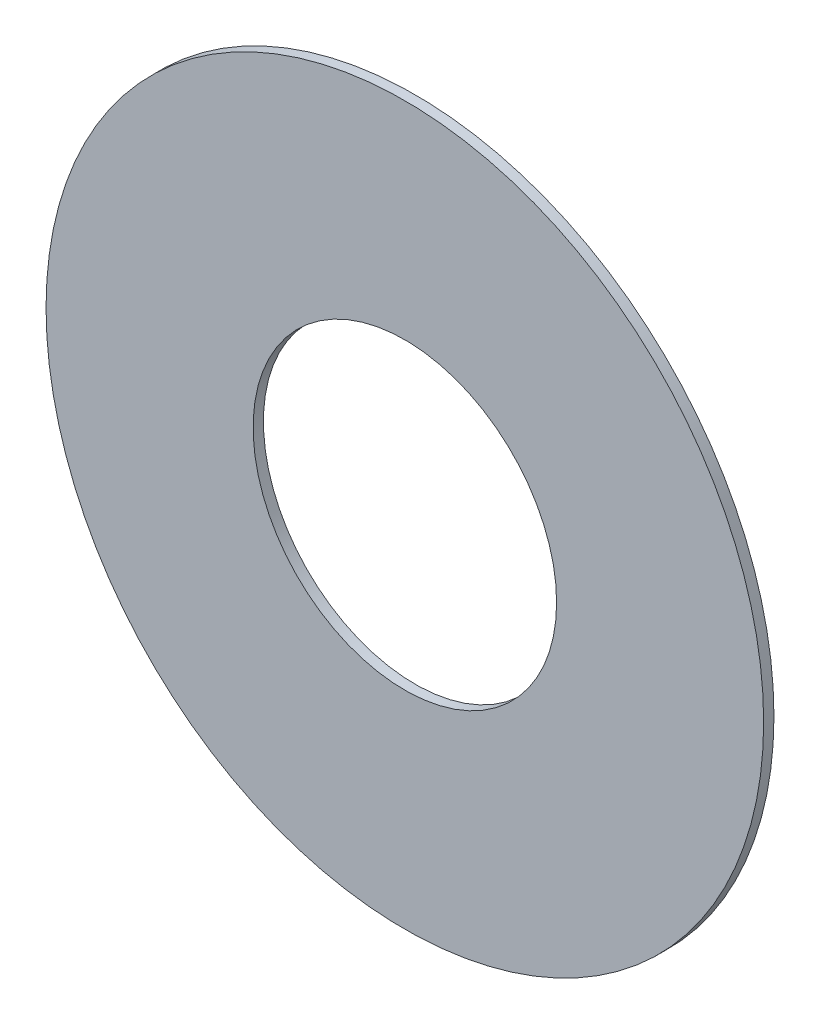
SolidWorks part; units mm, degrees
ref_plane "Спереди" through (0, 0, 0) normal (0, 0, 1) x (1, 0, 0)
ref_plane "Сверху" through (0, 0, 0) normal (0, 1, 0) x (1, 0, 0)
ref_plane "Справа" through (0, 0, 0) normal (1, 0, 0) x (0, 0, -1)
sketch "Эскиз1" plane through (0, 0, 0) normal (0, 0, 1) x (1, 0, 0)
  circle A0 centre (0, 0) radius 69.7538
  circle A1 centre (0, 0) radius 29.5
extrude "Printed_guard" add sketch "Эскиз1" along normal blind 2 from offset 42.5
